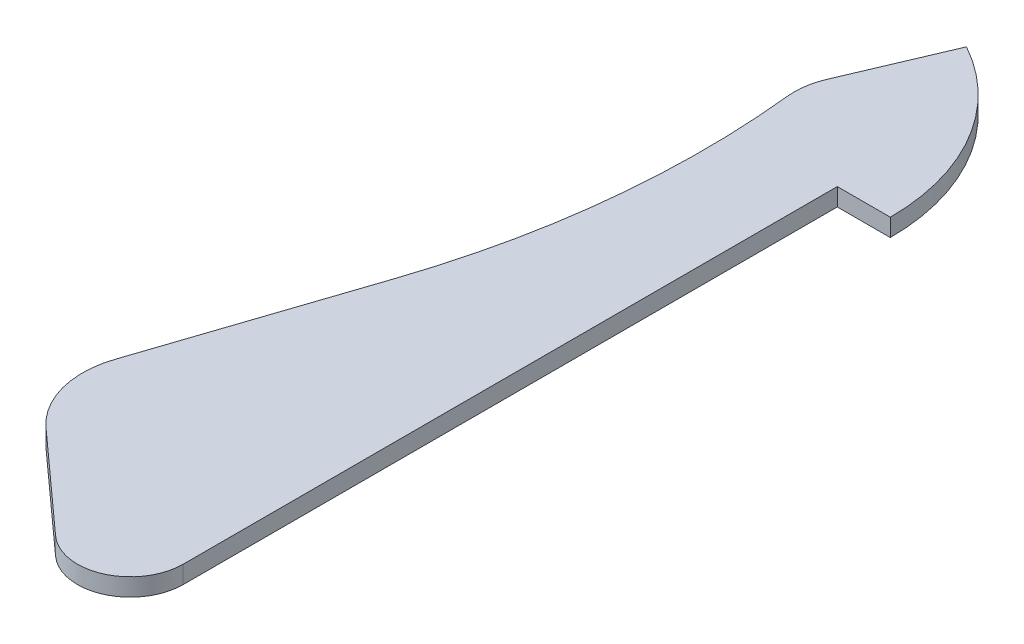
SolidWorks part; units mm, degrees
material "Acrylic (Medium-high impact)"
ref_plane "Front Plane" through (0, 0, 0) normal (0, 0, 1) x (1, 0, 0)
ref_plane "Top Plane" through (0, 0, 0) normal (0, 1, 0) x (1, 0, 0)
ref_plane "Right Plane" through (0, 0, 0) normal (1, 0, 0) x (0, 0, -1)
sketch "Sketch1" plane through (0, 0, 0) normal (0, 1, 0) x (1, 0, 0)
  line L12 (0, 0) -> (0, -234.95)
  line L19 (0, -234.95) -> (-31.75, -249.0611) construction
  line L20 (-31.75, -249.0611) -> (-67.1399, -217.1119)
  line L21 (-75.9849, -183.5046) -> (-50.8, -107.95)
  line L22 (-37.0485, 18.9889) -> (-39.0627, 37.9321) construction
  line L23 (-37.0485, 18.9889) -> (-56.0985, 18.9889) construction
  line L24 (0, 0) -> (19.05, 0)
  line L25 (-20.2598, 66.675) -> (-35.1662, 31.6121)
  line L28 (19.05, 0) -> (19.05, -19.05) construction
  arc A8 (0, -234.95) -> (-31.75, -249.0611) centre (-19.0108, -234.95) cw
  arc A12 (-50.8, -107.95) -> (-37.0485, 18.9889) centre (-336.1943, -12.8186) ccw
  arc A13 (-67.1399, -217.1119) -> (-75.9849, -183.5046) centre (-45.8642, -193.5448) cw
  arc A14 (19.05, 0) -> (-20.2598, 66.675) centre (-57.15, 0) ccw
  arc A18 (-35.1662, 31.6121) -> (-37.0485, 18.9889) centre (-11.7909, 21.6745) ccw
  point P15 (-82.55, -203.2)
  dimension "D5" = 82.55
  dimension "D2" = 25.4
  dimension "D11" = 38.1
  dimension "D12" = 18.9889
  dimension "D8" = 31.75
  dimension "D9" = 19.05
  dimension "D13" = 76.2
  dimension "D1" = 234.95
  dimension "D3" = 107.95
  dimension "D4" = 203.2
  dimension "D6" = 50.8
  dimension "D7" = 31.75
  dimension "D10" = 66.675
extrude "Boss-Extrude1" add sketch "Sketch1" along normal blind 6.35
ref_plane "Plane1" through (0, 0, 253.9608) normal (0, 0, 1) x (1, 0, 0)
